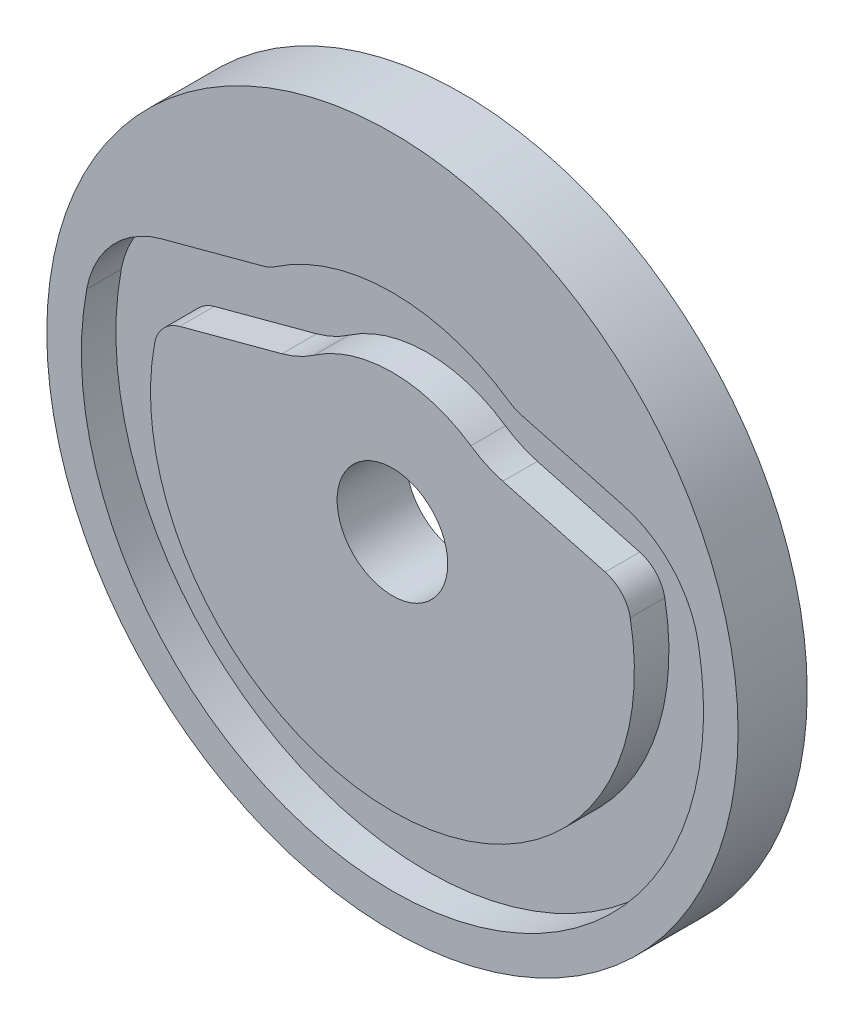
SolidWorks part; units mm, degrees
ref_plane "前视基准面" through (0, 0, 0) normal (0, 0, 1) x (1, 0, 0)
ref_plane "上视基准面" through (0, 0, 0) normal (0, 1, 0) x (1, 0, 0)
ref_plane "右视基准面" through (0, 0, 0) normal (1, 0, 0) x (0, 0, -1)
sketch "草图1" plane through (0, 0, 0) normal (0, 0, 1) x (1, 0, 0)
  circle A0 centre (0, 0) radius 50
  dimension "D1" = 100
extrude "凸台-拉伸1" add sketch "草图1" along normal blind 10
sketch "草图2" plane through (0, 0, 10) normal (0, 0, 1) x (1, 0, 0)
  line L0 (0, 0) -> (0, 20.2157) construction
  line L1 (0, 0) -> (34.641, 20) construction
  line L2 (21.6506, 12.5) -> (34.641, 20) construction
  line L3 (17.2643, 19.1657) -> (32.0725, 15.1979)
  line L4 (-17.2643, 19.1657) -> (-32.0725, 15.1979)
  arc A0 (14.1804, 20.5892) -> (-14.1804, 20.5892) centre (0, 0) ccw
  arc A1 (-39.3124, 7.3848) -> (39.3124, 7.3848) centre (0, 0) ccw
  arc A2 (-32.0725, 15.1979) -> (-39.3124, 7.3848) centre (-29.4843, 5.5386) ccw
  arc A3 (-17.2643, 19.1657) -> (-14.1804, 20.5892) centre (-19.8525, 28.8249) ccw
  arc A4 (17.2643, 19.1657) -> (14.1804, 20.5892) centre (19.8525, 28.8249) cw
  arc A5 (32.0725, 15.1979) -> (39.3124, 7.3848) centre (29.4843, 5.5386) cw
  point P6 (21.6506, 12.5)
  point P11 (28.1458, 16.25)
  point P12 (29.7229, 26.7684)
  point P14 (24.3185, 5.7976)
  point P15 (17.3205, 18.1307)
  point P18 (-37.5718, 13.7243)
  point P21 (-15.455, 19.6505)
  point P24 (15.455, 19.6505)
  point P27 (37.5718, 13.7243)
  dimension "D1" = 50
  dimension "D2" = 80
  dimension "D5" = 10
  dimension "D3" = 60
  dimension "D4" = 45
extrude "切除-拉伸-薄壁1" cut sketch "草图2" against normal blind 5 thin thin type mid plane wall 10
sketch "草图3" plane through (0, 0, 5) normal (0, 0, 1) x (1, 0, 0)
  line L2 (32.0725, 15.1979) -> (17.2643, 19.1657)
  line L3 (-17.2643, 19.1657) -> (-32.0725, 15.1979)
  line L4 (32.0725, 15.1979) -> (17.2643, 19.1657)
  line L5 (-17.2643, 19.1657) -> (-32.0725, 15.1979)
  arc A6 (39.3124, 7.3848) -> (32.0725, 15.1979) centre (29.4843, 5.5386) ccw
  arc A7 (-39.3124, 7.3848) -> (39.3124, 7.3848) centre (0, 0) ccw
  arc A8 (-32.0725, 15.1979) -> (-39.3124, 7.3848) centre (-29.4843, 5.5386) ccw
  arc A9 (-17.2643, 19.1657) -> (-14.1804, 20.5892) centre (-19.8525, 28.8249) ccw
  arc A10 (14.1804, 20.5892) -> (-14.1804, 20.5892) centre (0, 0) ccw
  arc A11 (14.1804, 20.5892) -> (17.2643, 19.1657) centre (19.8525, 28.8249) ccw
  arc A12 (39.3124, 7.3848) -> (32.0725, 15.1979) centre (29.4843, 5.5386) ccw
  arc A13 (-39.3124, 7.3848) -> (39.3124, 7.3848) centre (0, 0) ccw
  arc A14 (-32.0725, 15.1979) -> (-39.3124, 7.3848) centre (-29.4843, 5.5386) ccw
  arc A15 (-17.2643, 19.1657) -> (-14.1804, 20.5892) centre (-19.8525, 28.8249) ccw
  arc A16 (14.1804, 20.5892) -> (-14.1804, 20.5892) centre (0, 0) ccw
  arc A17 (14.1804, 20.5892) -> (17.2643, 19.1657) centre (19.8525, 28.8249) ccw
  dimension "D1" = 0
sketch "草图4" plane through (0, 0, 10) normal (0, 0, 1) x (1, 0, 0)
  circle A0 centre (0, 0) radius 8
  dimension "D1" = 16
extrude "切除-拉伸1" cut sketch "草图4" against normal through all
